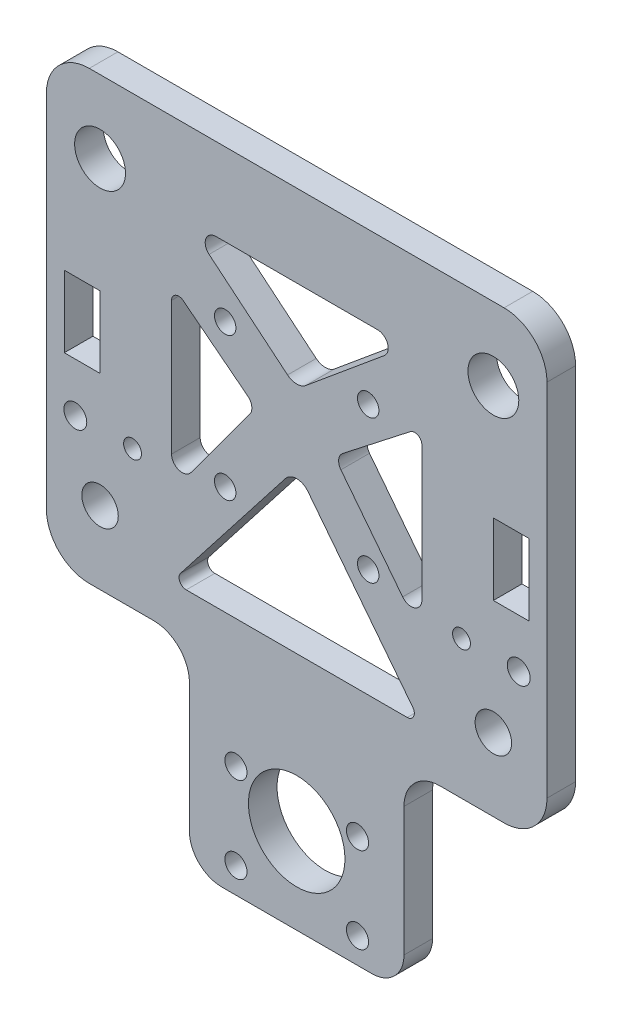
SolidWorks part; units mm, degrees
ref_plane "Спереди" through (0, 0, 0) normal (0, 0, 1) x (1, 0, 0)
ref_plane "Сверху" through (0, 0, 0) normal (0, 1, 0) x (1, 0, 0)
ref_plane "Справа" through (0, 0, 0) normal (1, 0, 0) x (0, 0, -1)
sketch "Model" plane through (0, 0, 0) normal (0, 0, 1) x (1, 0, 0)
  line L0 (-32.5, 1.0025) -> (-27.5, 1.0025)
  line L1 (-27.5, 1.0025) -> (-27.5, 11.0025)
  line L2 (-27.5, 11.0025) -> (-32.5, 11.0025)
  line L3 (-32.5, 11.0025) -> (-32.5, 1.0025)
  line L4 (32.5, 11.0025) -> (27.5, 11.0025)
  line L5 (27.5, 11.0025) -> (27.5, 1.0025)
  line L6 (27.5, 1.0025) -> (32.5, 1.0025)
  line L7 (32.5, 1.0025) -> (32.5, 11.0025)
  line L8 (-29, 37.1928) -> (29, 37.1928)
  line L9 (35, 31.1928) -> (35, -19.1878)
  line L10 (29, -25.1878) -> (20, -25.1878)
  line L11 (15, -30.1878) -> (15, -48.1878)
  line L12 (10.5, -52.6878) -> (-10.5, -52.6878)
  line L13 (-15, -48.1878) -> (-15, -30.1878)
  line L14 (-20, -25.1878) -> (-29, -25.1878)
  line L15 (-35, -19.1878) -> (-35, 31.1928)
  line L16 (-15.452, -19.1878) -> (15.452, -19.1878)
  line L17 (16.2406, -17.5728) -> (1.5771, 1.2299)
  line L18 (-1.5771, 1.2299) -> (-16.2406, -17.5728)
  line L19 (6.1794, 6.1691) -> (14.8172, -4.9071)
  line L20 (17.5, -3.9846) -> (17.5, 14.8517)
  line L21 (15.885, 15.6403) -> (6.4398, 8.2743)
  line L22 (-17.5, 14.8517) -> (-17.5, -3.7682)
  line L23 (-14.7907, -4.6557) -> (-6.9686, 6.0025)
  line L24 (-6.9686, 6.0025) -> (-6.5893, 6.4888)
  line L25 (-6.8497, 8.594) -> (-15.885, 15.6403)
  line L26 (11.2964, 25.6923) -> (-11.2964, 25.6923)
  line L27 (-12.2544, 23.0381) -> (-1.2774, 13.9266)
  line L28 (1.2774, 13.9266) -> (12.2544, 23.0381)
  line L29 (-10, 16.0025) -> (10, 16.0025) construction
  circle A0 centre (-22.955, -5.8427) radius 1.25
  circle A1 centre (23.045, -5.8427) radius 1.25
  circle A2 centre (-30.955, -5.8427) radius 1.6
  circle A3 centre (31.045, -5.8427) radius 1.6
  circle A4 centre (-27.5, -15.0033) radius 2.55
  circle A5 centre (27.5, 27.0083) radius 3.556
  circle A6 centre (-27.5, 27.0083) radius 3.556
  circle A7 centre (27.5, -15.0033) radius 2.55
  circle A8 centre (-10, -3.9975) radius 1.5
  circle A9 centre (10, -3.9975) radius 1.5
  circle A10 centre (-10, 16.0025) radius 1.5
  circle A11 centre (10, 16.0025) radius 1.5
  circle A12 centre (-8.5, -37.0878) radius 1.55
  circle A13 centre (8.5, -37.0878) radius 1.55
  circle A14 centre (-8.5, -49.0878) radius 1.55
  circle A15 centre (0, -40.6878) radius 6.75
  circle A16 centre (8.5, -49.0878) radius 1.55
  arc A102 (-29, 37.1928) -> (-35, 31.1928) centre (-29, 31.1928) ccw
  arc A103 (35, 31.1928) -> (29, 37.1928) centre (29, 31.1928) ccw
  arc A104 (29, -25.1878) -> (35, -19.1878) centre (29, -19.1878) ccw
  arc A105 (20, -25.1878) -> (15, -30.1878) centre (20, -30.1878) ccw
  arc A106 (10.5, -52.6878) -> (15, -48.1878) centre (10.5, -48.1878) ccw
  arc A107 (-15, -48.1878) -> (-10.5, -52.6878) centre (-10.5, -48.1878) ccw
  arc A108 (-15, -30.1878) -> (-20, -25.1878) centre (-20, -30.1878) ccw
  arc A109 (-35, -19.1878) -> (-29, -25.1878) centre (-29, -19.1878) ccw
  arc A110 (15.452, -19.1878) -> (16.2406, -17.5728) centre (15.452, -18.1878) ccw
  arc A111 (1.5771, 1.2299) -> (-1.5771, 1.2299) centre (0, 0) ccw
  arc A112 (-16.2406, -17.5728) -> (-15.452, -19.1878) centre (-15.452, -18.1878) ccw
  arc A113 (14.8172, -4.9071) -> (17.5, -3.9846) centre (16, -3.9846) ccw
  arc A114 (17.5, 14.8517) -> (15.885, 15.6403) centre (16.5, 14.8517) ccw
  arc A115 (6.4398, 8.2743) -> (6.1794, 6.1691) centre (7.3622, 7.0915) ccw
  arc A116 (-17.5, -3.7682) -> (-14.7907, -4.6557) centre (-16, -3.7682) ccw
  arc A117 (-6.5893, 6.4888) -> (-6.8497, 8.594) centre (-7.7722, 7.4112) ccw
  arc A118 (-15.885, 15.6403) -> (-17.5, 14.8517) centre (-16.5, 14.8517) ccw
  arc A119 (-11.2964, 25.6923) -> (-12.2544, 23.0381) centre (-11.2964, 24.1923) ccw
  arc A120 (-1.2774, 13.9266) -> (1.2774, 13.9266) centre (0, 15.4655) ccw
  arc A121 (12.2544, 23.0381) -> (11.2964, 25.6923) centre (11.2964, 24.1923) ccw
extrude "Бобышка-Вытянуть1" add sketch "Model" along normal blind 4
